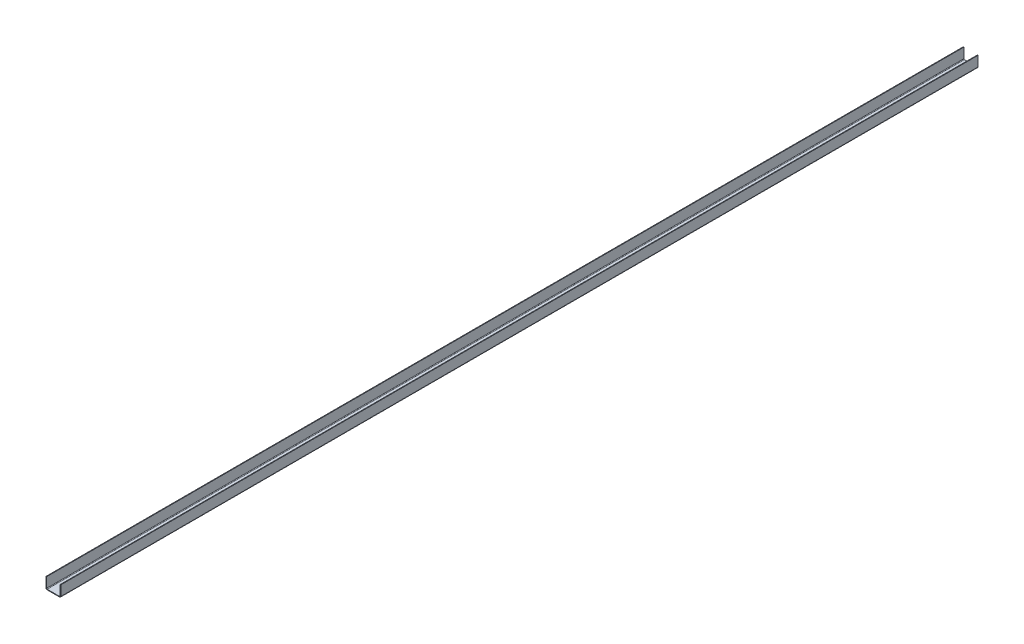
SolidWorks part; units mm, degrees
material "AISI 304"
ref_plane "Front Plane" through (0, 0, 0) normal (0, 0, 1) x (1, 0, 0)
ref_plane "Top Plane" through (0, 0, 0) normal (0, 1, 0) x (1, 0, 0)
ref_plane "Right Plane" through (0, 0, 0) normal (1, 0, 0) x (0, 0, -1)
sketch "Sketch1" plane through (0, 0, 0) normal (0, 0, 1) x (1, 0, 0)
  line L0 (16.84, 2) -> (16.84, -23)
  line L1 (13.84, -26) -> (-17.16, -26)
  line L2 (-20.16, -23) -> (-20.16, 2)
  arc A0 (16.84, -23) -> (13.84, -26) centre (13.84, -23) cw
  arc A1 (-20.16, -23) -> (-17.16, -26) centre (-17.16, -23) ccw
  point P8 (16.84, -26)
  point P11 (-20.16, -26)
  dimension "D4" = 3
  dimension "D1" = 28
  dimension "D2" = 28
  dimension "D3" = 37
extrude "Extrude-Thin1" add sketch "Sketch1" along normal blind 2300 thin
sketch "Sketch2" plane through (0, -24.5, 0) normal (0, 1, 0) x (1, 0, 0)
  line L0 (13.84, 0) -> (-17.16, 0) construction
  circle A0 centre (0, -383) radius 3.25
  dimension "D1" = 6.5
  dimension "D2" = 383
extrude "Cut-Extrude1" cut sketch "Sketch2" against normal blind 10
pattern_linear "LPattern1" count 3 spacing 766 along (0, 0, 1) of "Cut-Extrude1"
